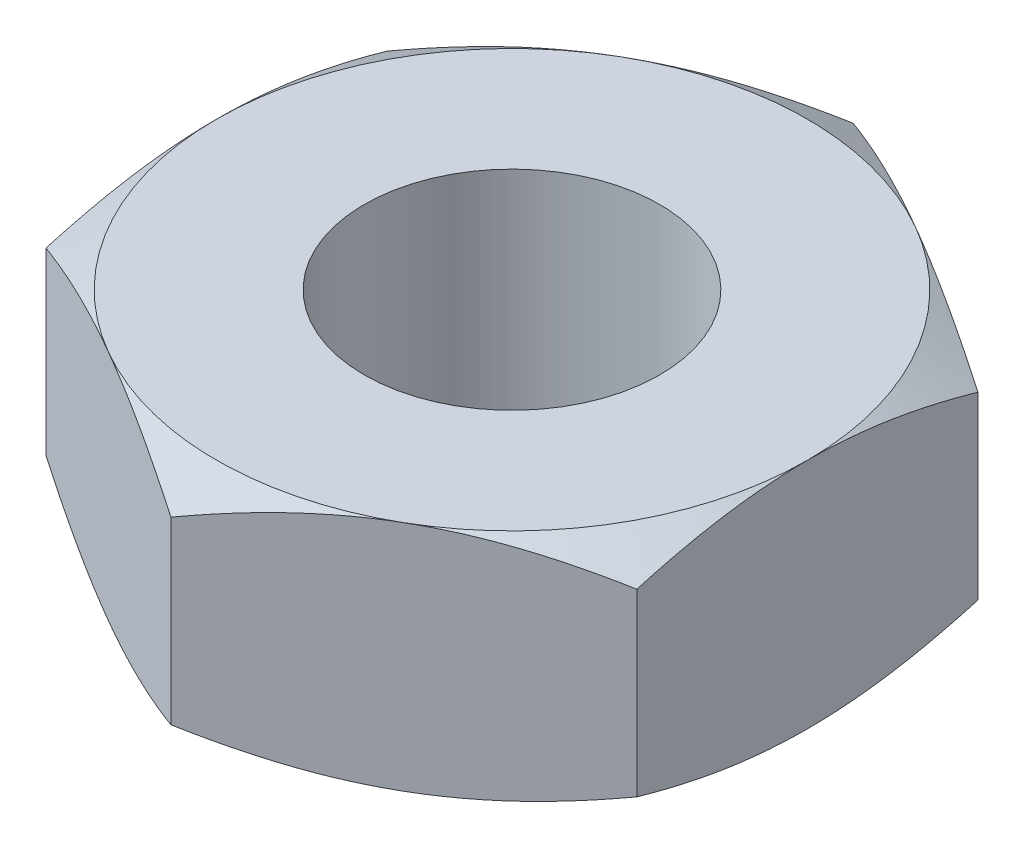
SolidWorks part; units mm, degrees
ref_plane "Front Plane" through (0, 0, 0) normal (0, 0, 1) x (1, 0, 0)
ref_plane "Top Plane" through (0, 0, 0) normal (0, 1, 0) x (1, 0, 0)
ref_plane "Right Plane" through (0, 0, 0) normal (1, 0, 0) x (0, 0, -1)
sketch "Sketch1" plane through (0, 0, 0) normal (0, 1, 0) x (1, 0, 0)
  line L1 (-12.7, 7.3323) -> (-12.7, -7.3323)
  line L2 (-12.7, -7.3323) -> (0, -14.6647)
  line L3 (0, -14.6647) -> (12.7, -7.3323)
  line L4 (12.7, -7.3323) -> (12.7, 7.3323)
  line L5 (12.7, 7.3323) -> (0, 14.6647)
  line L6 (0, 14.6647) -> (-12.7, 7.3323)
  circle A0 centre (0, 0) radius 12.7 construction
  dimension "D1" = 25.4
extrude "Boss-Extrude1" add sketch "Sketch1" along normal mid plane 10
sketch "Sketch2" plane through (0, 5, 0) normal (0, 1, 0) x (1, 0, 0)
  circle A0 centre (0, 0) radius 6.35
  dimension "D1" = 12.7
extrude "Cut-Extrude1" cut sketch "Sketch2" against normal through all
cosmetic thread "Cosmetic Thread1" parameters "D2"=14.2875
sketch "Sketch3" plane through (0, 5, 0) normal (0, 1, 0) x (1, 0, 0)
  circle A0 centre (0, 0) radius 12.7
extrude "Cut-Extrude2" cut sketch "Sketch3" against normal through all draft 60 flip side to cut
mirror "Mirror1" about plane through (0, 0, 0) normal (0, 1, 0) of "Cut-Extrude2"
